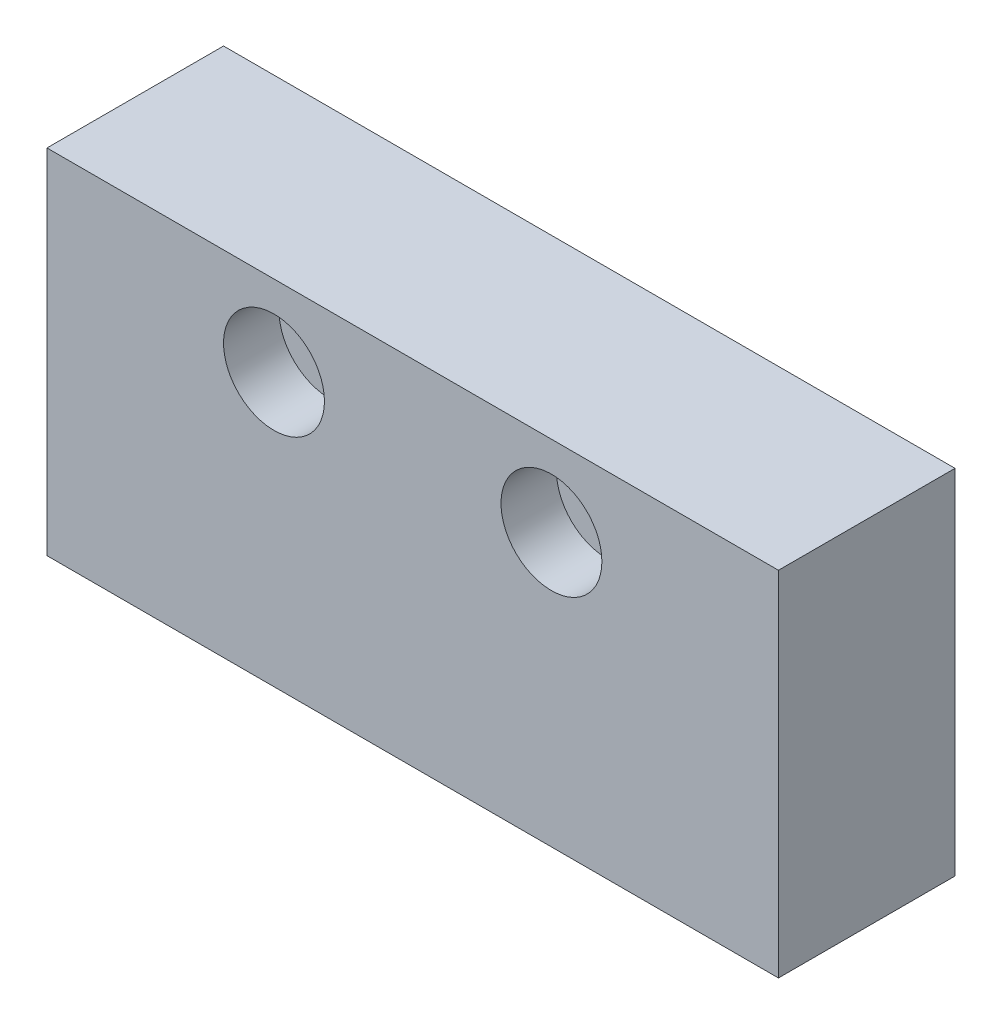
SolidWorks part; units mm, degrees
ref_plane "Front Plane" through (0, 0, 0) normal (0, 0, 1) x (1, 0, 0)
ref_plane "Top Plane" through (0, 0, 0) normal (0, 1, 0) x (1, 0, 0)
ref_plane "Right Plane" through (0, 0, 0) normal (1, 0, 0) x (0, 0, -1)
sketch "Sketch1" plane through (0, 0, 0) normal (0, 0, 1) x (1, 0, 0)
  line L1 (-29, -14) -> (29, -14)
  line L2 (-29, -14) -> (-29, 14)
  line L3 (-29, 14) -> (29, 14)
  line L4 (29, -14) -> (29, 14)
  line L5 (-29, -14) -> (29, 14) construction
  line L6 (-29, 14) -> (29, -14) construction
  point P0 (0, 0)
  dimension "D1" = 28
  dimension "D2" = 58
extrude "Boss-Extrude1" add sketch "Sketch1" along normal mid plane 14
hole_wizard "CBORE for M4 Hex Socket Head Cap Screw1" positions "Sketch2" profile "Sketch4" counterbore size "M4" standard "ISO" end condition through all
sketch "Sketch2" plane through (0, 0, 7) normal (0, 0, 1) x (1, 0, 0)
  line L0 (-11, 7.6) -> (11, 7.6) construction
  line L2 (0, 0) -> (0, 7.6) construction
  line L4 (29, 14) -> (-29, 14) construction
  point P0 (-11, 7.6)
  point P2 (11, 7.6)
  dimension "D1" = 22
  dimension "D2" = 6.4
sketch "Sketch4" plane through (-11, 7.6, 7) normal (1, 0, 0) x (0, -1, 0)
  line L0 (0, 0) -> (0, 14)
  line L1 (0, 14) -> (2.15, 14)
  line L3 (2.15, 14) -> (2.15, 4.4)
  line L4 (2.15, 4.4) -> (4, 4.4)
  line L5 (4, 4.4) -> (4, 0)
  line L7 (4, 0) -> (0, 0)
  line L11 (0, -6.35) -> (0, 107.95) construction
  dimension "Thru Hole Dia." = 4.3
  dimension "Thru Hole Depth" = 14
  dimension "C'Bore Dia." = 8
  dimension "C'Bore Depth" = 4.4
